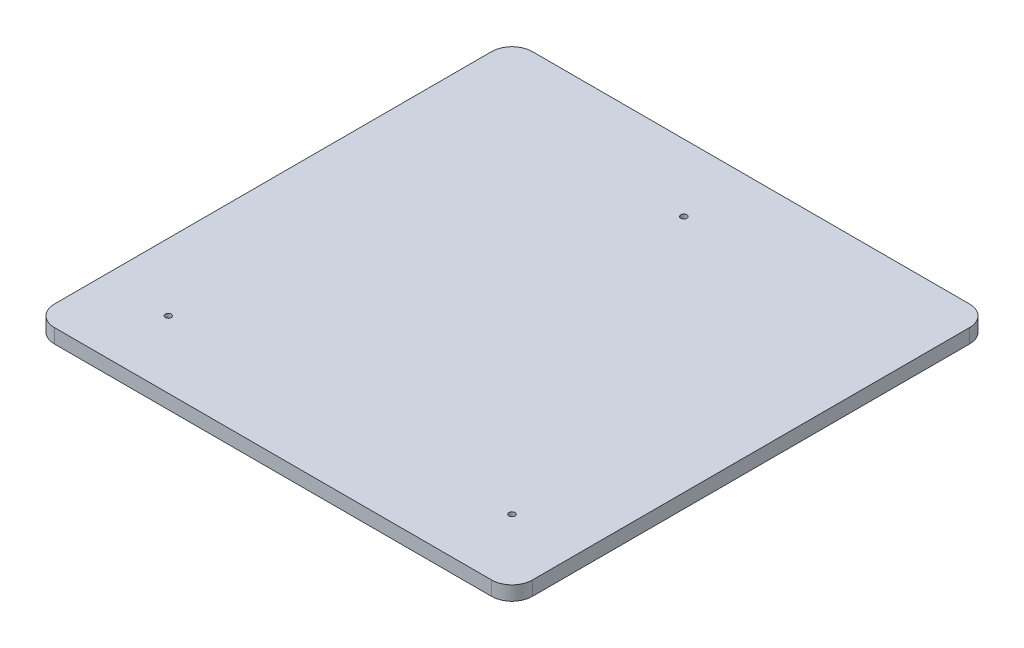
SolidWorks part; units mm, degrees
ref_plane "Front Plane" through (0, 0, 0) normal (0, 0, 1) x (1, 0, 0)
ref_plane "Top Plane" through (0, 0, 0) normal (0, 1, 0) x (1, 0, 0)
ref_plane "Right Plane" through (0, 0, 0) normal (1, 0, 0) x (0, 0, -1)
sketch "Sketch1" plane through (0, 0, 0) normal (0, 1, 0) x (1, 0, 0)
  line L0 (0, 84.5) -> (0, -84.5) construction
  line L1 (-117.5, -117.5) -> (117.5, -117.5)
  line L2 (-117.5, -117.5) -> (-117.5, 117.5)
  line L3 (-117.5, 117.5) -> (117.5, 117.5)
  line L4 (117.5, -117.5) -> (117.5, 117.5)
  line L5 (-117.5, -117.5) -> (117.5, 117.5) construction
  line L6 (-117.5, 117.5) -> (117.5, -117.5) construction
  line L7 (0, 84.5) -> (-84.5, -84.5) construction
  line L8 (-84.5, -84.5) -> (84.5, -84.5) construction
  line L9 (84.5, -84.5) -> (0, 84.5) construction
  circle A0 centre (0, 84.5) radius 1.5
  circle A1 centre (84.5, -84.5) radius 1.5
  circle A2 centre (-84.5, -84.5) radius 1.5
  point P0 (0, 0)
  dimension "D4" = 3
  dimension "D1" = 235
  dimension "D2" = 235
  dimension "D3" = 169
extrude "Boss-Extrude1" add sketch "Sketch1" along normal blind 7
fillet "Fillet1" radius 10 4 edges at (-117.5, 3.5, 117.5) (-117.5, 3.5, -117.5) (117.5, 3.5, -117.5) (117.5, 3.5, 117.5)
